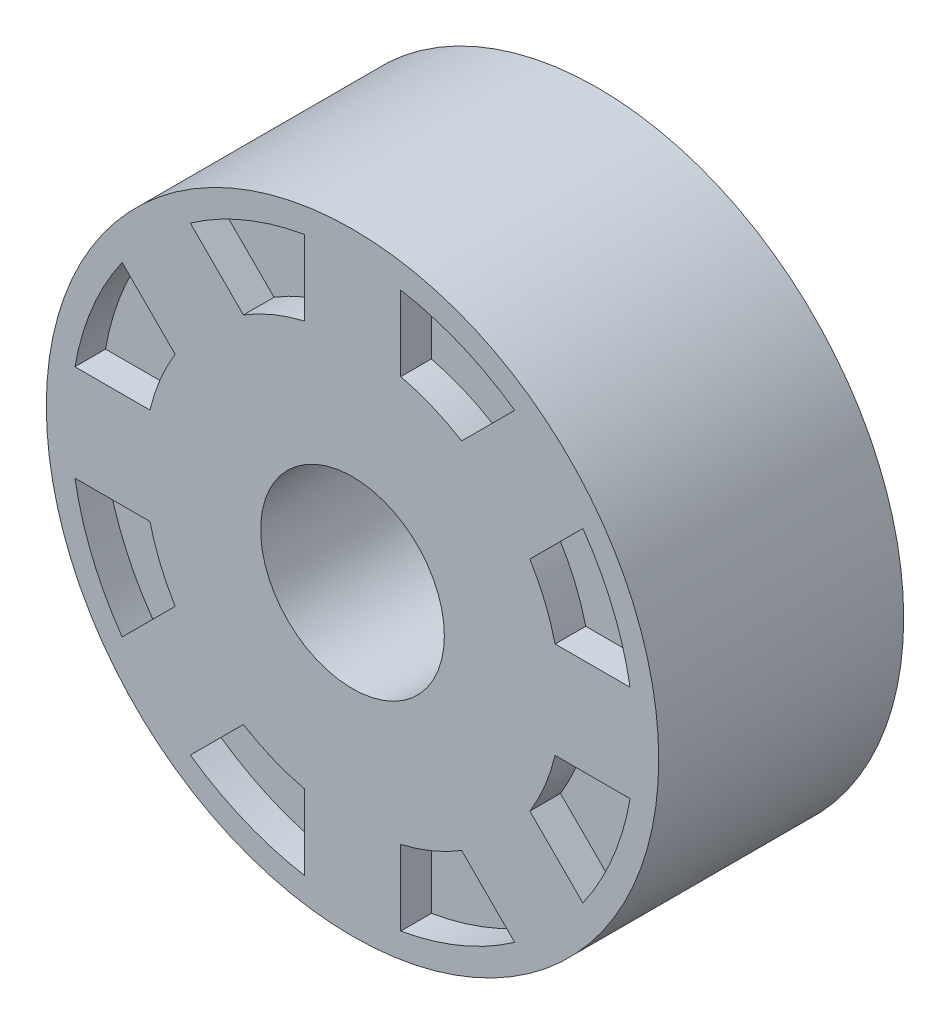
SolidWorks part; units mm, degrees
ref_plane "Front Plane" through (0, 0, 0) normal (0, 0, 1) x (1, 0, 0)
ref_plane "Top Plane" through (0, 0, 0) normal (0, 1, 0) x (1, 0, 0)
ref_plane "Right Plane" through (0, 0, 0) normal (1, 0, 0) x (0, 0, -1)
sketch "Sketch1" plane through (0, 0, 0) normal (0, 0, 1) x (1, 0, 0)
  circle A0 centre (0, 0) radius 63.5
  circle A1 centre (0, 0) radius 19.05
  dimension "D1" = 127
  dimension "D2" = 38.1
extrude "Boss-Extrude1" add sketch "Sketch1" along normal mid plane 50.8
sketch "Sketch3" plane through (0, 0, 25.4) normal (0, 0, 1) x (1, 0, 0)
  line L0 (58.42, 0) -> (43.18, 0) construction
  line L1 (0, -58.42) -> (0, -43.18) construction
  line L2 (-41.3092, -41.3092) -> (-30.5329, -30.5329) construction
  line L3 (41.3092, -41.3092) -> (30.5329, -30.5329) construction
  line L4 (-30.5329, 30.5329) -> (-41.3092, 41.3092) construction
  line L5 (-43.18, 0) -> (-58.42, 0) construction
  line L6 (30.5329, 30.5329) -> (41.3092, 41.3092) construction
  line L7 (0, 43.18) -> (0, 58.42) construction
  line L8 (36.7739, 22.6317) -> (47.7706, 33.6284)
  line L9 (57.5578, 10) -> (42.0061, 10)
  line L10 (47.7706, -33.6284) -> (36.7739, -22.6317)
  line L11 (10, -57.5578) -> (10, -42.0061)
  line L12 (-33.6284, -47.7706) -> (-22.6317, -36.7739)
  line L13 (-42.0061, 10) -> (-57.5578, 10)
  line L14 (22.6317, 36.7739) -> (33.6284, 47.7706)
  line L15 (57.5578, -10) -> (42.0061, -10)
  line L16 (33.6284, -47.7706) -> (22.6317, -36.7739)
  line L17 (-10, -57.5578) -> (-10, -42.0061)
  line L18 (-47.7706, -33.6284) -> (-36.7739, -22.6317)
  line L19 (-42.0061, -10) -> (-57.5578, -10)
  line L20 (-22.6317, 36.7739) -> (-33.6284, 47.7706)
  line L21 (-36.7739, 22.6317) -> (-47.7706, 33.6284)
  line L22 (10, 42.0061) -> (10, 57.5578)
  line L23 (-10, 42.0061) -> (-10, 57.5578)
  line L24 (37.6039, 23.4618) -> (48.3802, 34.2381) construction
  line L25 (23.4618, 37.6039) -> (34.2381, 48.3802) construction
  line L26 (58.42, 10) -> (43.18, 10) construction
  line L27 (58.42, -10) -> (43.18, -10) construction
  line L28 (48.3802, -34.2381) -> (37.6039, -23.4618) construction
  line L29 (34.2381, -48.3802) -> (23.4618, -37.6039) construction
  line L30 (10, -58.42) -> (10, -43.18) construction
  line L31 (-10, -58.42) -> (-10, -43.18) construction
  line L32 (-34.2381, -48.3802) -> (-23.4618, -37.6039) construction
  line L33 (-48.3802, -34.2381) -> (-37.6039, -23.4618) construction
  line L34 (-43.18, -10) -> (-58.42, -10) construction
  line L35 (-43.18, 10) -> (-58.42, 10) construction
  line L36 (-37.6039, 23.4618) -> (-48.3802, 34.2381) construction
  line L37 (-23.4618, 37.6039) -> (-34.2381, 48.3802) construction
  line L38 (-10, 43.18) -> (-10, 58.42) construction
  line L39 (10, 43.18) -> (10, 58.42) construction
  arc A0 (-10, 42.0061) -> (-22.6317, 36.7739) centre (0, 0) ccw
  arc A1 (-10, 57.5578) -> (-33.6284, 47.7706) centre (0, 0) ccw
  circle A2 centre (0, 0) radius 63.5 construction
  arc A3 (22.6317, 36.7739) -> (10, 42.0061) centre (0, 0) ccw
  arc A4 (33.6284, 47.7706) -> (10, 57.5578) centre (0, 0) ccw
  arc A5 (42.0061, 10) -> (36.7739, 22.6317) centre (0, 0) ccw
  arc A6 (57.5578, 10) -> (47.7706, 33.6284) centre (0, 0) ccw
  arc A7 (36.7739, -22.6317) -> (42.0061, -10) centre (0, 0) ccw
  arc A8 (47.7706, -33.6284) -> (57.5578, -10) centre (0, 0) ccw
  arc A9 (10, -42.0061) -> (22.6317, -36.7739) centre (0, 0) ccw
  arc A10 (10, -57.5578) -> (33.6284, -47.7706) centre (0, 0) ccw
  arc A11 (-22.6317, -36.7739) -> (-10, -42.0061) centre (0, 0) ccw
  arc A12 (-33.6284, -47.7706) -> (-10, -57.5578) centre (0, 0) ccw
  arc A13 (-42.0061, -10) -> (-36.7739, -22.6317) centre (0, 0) ccw
  arc A14 (-57.5578, -10) -> (-47.7706, -33.6284) centre (0, 0) ccw
  arc A15 (-36.7739, 22.6317) -> (-42.0061, 10) centre (0, 0) ccw
  arc A16 (-47.7706, 33.6284) -> (-57.5578, 10) centre (0, 0) ccw
  point P9 (0, 0)
  point P12 (0, 0)
  point P15 (0, 0)
  point P18 (0, 0)
  dimension "D1" = 5.08
  dimension "D2" = 86.36
  dimension "D3" = 10
  dimension "D4" = 10
  dimension "D5" = 10
  dimension "D6" = 10
  dimension "D7" = 10
  dimension "D8" = 10
extrude "Cut-Extrude1" cut sketch "Sketch3" against normal blind 6.35
sketch "Sketch4" plane through (0, 0, -25.4) normal (0, 0, -1) x (-1, 0, 0)
  line L0 (-36.7739, -22.6317) -> (-47.7706, -33.6284) construction
  line L1 (-57.5578, -10) -> (-42.0061, -10) construction
  line L2 (-10, -42.0061) -> (-10, -57.5578) construction
  line L3 (-33.6284, -47.7706) -> (-22.6317, -36.7739) construction
  line L4 (22.6317, -36.7739) -> (33.6284, -47.7706) construction
  line L5 (10, -57.5578) -> (10, -42.0061) construction
  line L6 (42.0061, -10) -> (57.5578, -10) construction
  line L7 (47.7706, -33.6284) -> (36.7739, -22.6317) construction
  line L8 (36.7739, 22.6317) -> (47.7706, 33.6284) construction
  line L9 (57.5578, 10) -> (42.0061, 10) construction
  line L10 (10, 42.0061) -> (10, 57.5578) construction
  line L11 (33.6284, 47.7706) -> (22.6317, 36.7739) construction
  line L12 (-22.6317, 36.7739) -> (-33.6284, 47.7706) construction
  line L13 (-10, 57.5578) -> (-10, 42.0061) construction
  line L14 (-42.0061, 10) -> (-57.5578, 10) construction
  line L15 (-47.7706, 33.6284) -> (-36.7739, 22.6317) construction
  line L16 (-36.7739, -22.6317) -> (-47.7706, -33.6284)
  line L17 (-57.5578, -10) -> (-42.0061, -10)
  line L18 (-10, -42.0061) -> (-10, -57.5578)
  line L19 (-33.6284, -47.7706) -> (-22.6317, -36.7739)
  line L20 (22.6317, -36.7739) -> (33.6284, -47.7706)
  line L21 (10, -57.5578) -> (10, -42.0061)
  line L22 (42.0061, -10) -> (57.5578, -10)
  line L23 (47.7706, -33.6284) -> (36.7739, -22.6317)
  line L24 (36.7739, 22.6317) -> (47.7706, 33.6284)
  line L25 (57.5578, 10) -> (42.0061, 10)
  line L26 (10, 42.0061) -> (10, 57.5578)
  line L27 (33.6284, 47.7706) -> (22.6317, 36.7739)
  line L28 (-22.6317, 36.7739) -> (-33.6284, 47.7706)
  line L29 (-10, 57.5578) -> (-10, 42.0061)
  line L30 (-42.0061, 10) -> (-57.5578, 10)
  line L31 (-47.7706, 33.6284) -> (-36.7739, 22.6317)
  arc A0 (-42.0061, -10) -> (-36.7739, -22.6317) centre (0, 0) ccw construction
  arc A1 (-57.5578, -10) -> (-47.7706, -33.6284) centre (0, 0) ccw construction
  arc A2 (-22.6317, -36.7739) -> (-10, -42.0061) centre (0, 0) ccw construction
  arc A3 (-33.6284, -47.7706) -> (-10, -57.5578) centre (0, 0) ccw construction
  arc A4 (10, -42.0061) -> (22.6317, -36.7739) centre (0, 0) ccw construction
  arc A5 (10, -57.5578) -> (33.6284, -47.7706) centre (0, 0) ccw construction
  arc A6 (36.7739, -22.6317) -> (42.0061, -10) centre (0, 0) ccw construction
  arc A7 (47.7706, -33.6284) -> (57.5578, -10) centre (0, 0) ccw construction
  arc A8 (42.0061, 10) -> (36.7739, 22.6317) centre (0, 0) ccw construction
  arc A9 (57.5578, 10) -> (47.7706, 33.6284) centre (0, 0) ccw construction
  arc A10 (22.6317, 36.7739) -> (10, 42.0061) centre (0, 0) ccw construction
  arc A11 (33.6284, 47.7706) -> (10, 57.5578) centre (0, 0) ccw construction
  arc A12 (-10, 42.0061) -> (-22.6317, 36.7739) centre (0, 0) ccw construction
  arc A13 (-10, 57.5578) -> (-33.6284, 47.7706) centre (0, 0) ccw construction
  arc A14 (-36.7739, 22.6317) -> (-42.0061, 10) centre (0, 0) ccw construction
  arc A15 (-47.7706, 33.6284) -> (-57.5578, 10) centre (0, 0) ccw construction
  arc A16 (-42.0061, -10) -> (-36.7739, -22.6317) centre (0, 0) ccw
  arc A17 (-57.5578, -10) -> (-47.7706, -33.6284) centre (0, 0) ccw
  arc A18 (-22.6317, -36.7739) -> (-10, -42.0061) centre (0, 0) ccw
  arc A19 (-33.6284, -47.7706) -> (-10, -57.5578) centre (0, 0) ccw
  arc A20 (10, -42.0061) -> (22.6317, -36.7739) centre (0, 0) ccw
  arc A21 (10, -57.5578) -> (33.6284, -47.7706) centre (0, 0) ccw
  arc A22 (36.7739, -22.6317) -> (42.0061, -10) centre (0, 0) ccw
  arc A23 (47.7706, -33.6284) -> (57.5578, -10) centre (0, 0) ccw
  arc A24 (42.0061, 10) -> (36.7739, 22.6317) centre (0, 0) ccw
  arc A25 (57.5578, 10) -> (47.7706, 33.6284) centre (0, 0) ccw
  arc A26 (22.6317, 36.7739) -> (10, 42.0061) centre (0, 0) ccw
  arc A27 (33.6284, 47.7706) -> (10, 57.5578) centre (0, 0) ccw
  arc A28 (-10, 42.0061) -> (-22.6317, 36.7739) centre (0, 0) ccw
  arc A29 (-10, 57.5578) -> (-33.6284, 47.7706) centre (0, 0) ccw
  arc A30 (-36.7739, 22.6317) -> (-42.0061, 10) centre (0, 0) ccw
  arc A31 (-47.7706, 33.6284) -> (-57.5578, 10) centre (0, 0) ccw
extrude "Cut-Extrude2" cut sketch "Sketch4" against normal blind 6.35
